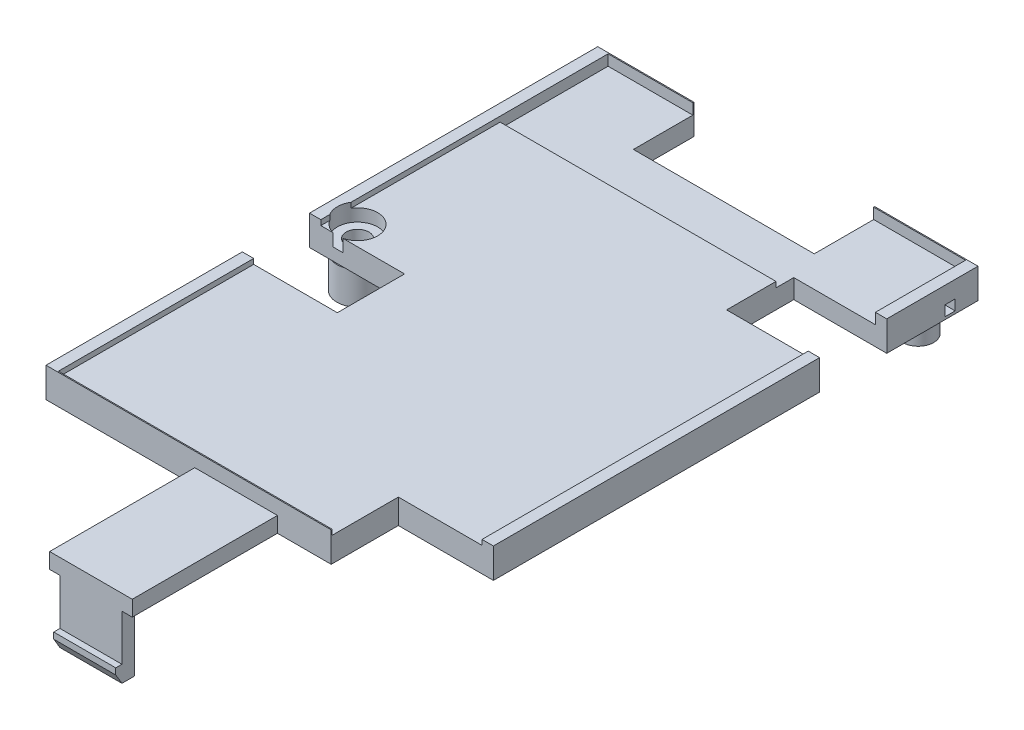
SolidWorks part; units mm, degrees
ref_plane "Front Plane" through (0, 0, 0) normal (0, 0, 1) x (1, 0, 0)
ref_plane "Top Plane" through (0, 0, 0) normal (0, 1, 0) x (1, 0, 0)
ref_plane "Right Plane" through (0, 0, 0) normal (1, 0, 0) x (0, 0, -1)
other "Configuration Table"
sketch "Sketch1" plane through (0, 0, 0) normal (0, 1, 0) x (1, 0, 0)
  line L1 (-18.4, 32.65) -> (18.4, 32.65)
  line L2 (-18.4, 32.65) -> (-18.4, -20.75)
  line L3 (-18.4, -20.75) -> (18.4, -20.75)
  line L4 (18.4, 32.65) -> (18.4, -20.75)
extrude "Tray" add sketch "Sketch1" along normal blind 2.89 from offset 4.75
sketch "Sketch2" plane through (0, 0, 0) normal (0, 1, 0) x (1, 0, 0)
  line L1 (-17.3, 32.55) -> (17.3, 32.55)
  line L2 (-17.3, 32.55) -> (-17.3, -20.65)
  line L3 (-17.3, -20.65) -> (17.3, -20.65)
  line L4 (17.3, 32.55) -> (17.3, -20.65)
extrude "Groove" cut sketch "Sketch2" along normal blind 0.6 from offset 7.14
sketch "Sketch3" plane through (0, 0, 0) normal (0, 1, 0) x (1, 0, 0)
  line L1 (-17.3, 32.55) -> (17.3, 32.55)
  line L2 (-17.3, 32.55) -> (-17.3, 22.1)
  line L3 (-17.3, 22.1) -> (17.3, 22.1)
  line L4 (17.3, 32.55) -> (17.3, 22.1)
extrude "Groove, protection-board end" cut sketch "Sketch3" along normal blind 0.55 from offset 6.6
sketch "Sketch4" plane through (0, 0, 0) normal (0, 1, 0) x (1, 0, 0)
  line L1 (-18.45, 4.75) -> (-9.2, 4.75)
  line L2 (-18.45, 4.75) -> (-18.45, -1.75)
  line L3 (-18.45, -1.75) -> (-9.2, -1.75)
  line L4 (-9.2, 4.75) -> (-9.2, -1.75)
  line L6 (9.4, 23.82) -> (18.45, 23.82)
  line L7 (9.4, 23.82) -> (9.4, 17.32)
  line L8 (9.4, 17.32) -> (18.45, 17.32)
  line L9 (18.45, 23.82) -> (18.45, 17.32)
  line L11 (9.2, -14.25) -> (18.45, -14.25)
  line L12 (9.2, -14.25) -> (9.2, -20.75)
  line L13 (9.2, -20.75) -> (18.45, -20.75)
  line L14 (18.45, -14.25) -> (18.45, -20.75)
extrude "S1-S3 and plugs" cut sketch "Sketch4" along normal blind 3.09 from offset 4.65
sketch "Sketch5" plane through (0, 0, 0) normal (0, 1, 0) x (1, 0, 0)
  line L1 (-9.1, 32.8) -> (8.4, 32.8)
  line L2 (-9.1, 32.8) -> (-9.1, 26.8)
  line L3 (-9.1, 26.8) -> (8.4, 26.8)
  line L4 (8.4, 32.8) -> (8.4, 26.8)
extrude "J4 and its flex" cut sketch "Sketch5" along normal blind 3.09 from offset 4.65
sketch "Sketch6" plane through (0, 0, 0) normal (0, 1, 0) x (1, 0, 0)
  line L1 (-4, -20.6) -> (4, -20.6)
  line L2 (-4, -20.6) -> (-4, -34.8)
  line L3 (-4, -34.8) -> (4, -34.8)
  line L4 (4, -20.6) -> (4, -34.8)
extrude "Arm" add sketch "Sketch6" along normal blind 1.5 from offset 4.75
sketch "Sketch7" plane through (0, 0, 0) normal (0, 1, 0) x (1, 0, 0)
  circle A0 centre (-15.64, 6.64) radius 2
extrude "Board screw foot" add sketch "Sketch7" along normal blind 3.16 from offset 1.6
sketch "Sketch8" plane through (0, 0, 0) normal (0, 1, 0) x (1, 0, 0)
  circle A0 centre (-15.64, 6.64) radius 1.1
extrude "Board screw hole" cut sketch "Sketch8" along normal blind 6.24 from offset 1.5
sketch "Sketch9" plane through (0, 0, 0) normal (0, 1, 0) x (1, 0, 0)
  circle A0 centre (-15.64, 6.64) radius 1.95
extrude "Board screw counterbore" cut sketch "Sketch9" along normal blind 1.8 from offset 5.94
sketch "Sketch10" plane through (0, 0, 0) normal (0, 1, 0) x (1, 0, 0)
  circle A0 centre (15.32, 29.94) radius 1.5
extrude "Mic tube" add sketch "Sketch10" along normal blind 2.96 from offset 1.8
sketch "Sketch11" plane through (0, 0, 0) normal (0, 1, 0) x (1, 0, 0)
  circle A0 centre (15.32, 29.94) radius 0.5
extrude "Mic bore" cut sketch "Sketch11" along normal blind 4.3 from offset 1.7
sketch "Sketch12" plane through (0, 0, 0) normal (0, 1, 0) x (1, 0, 0)
  line L1 (14.82, 30.44) -> (18.5, 30.44)
  line L2 (14.82, 30.44) -> (14.82, 29.44)
  line L3 (14.82, 29.44) -> (18.5, 29.44)
  line L4 (18.5, 30.44) -> (18.5, 29.44)
extrude "Mic duct" cut sketch "Sketch12" along normal blind 1 from offset 5
sketch "Sketch13" plane through (0, 0, 0) normal (1, 0, 0) x (0, 0, -1)
  line L0 (-33.6, 5.25) -> (-34.8, 5.25)
  line L1 (-34.8, 5.25) -> (-34.8, 0.3)
  line L2 (-34.8, 0.3) -> (-35.4, 0.3)
  line L3 (-35.4, 0.3) -> (-35.4, -0.3)
  line L4 (-35.4, -0.3) -> (-34.8, -1.3)
  line L5 (-34.8, -1.3) -> (-33.6, -1.3)
  line L6 (-33.6, -1.3) -> (-33.6, 5.25)
extrude "Snap" add sketch "Sketch13" along normal blind 6 from offset 3
